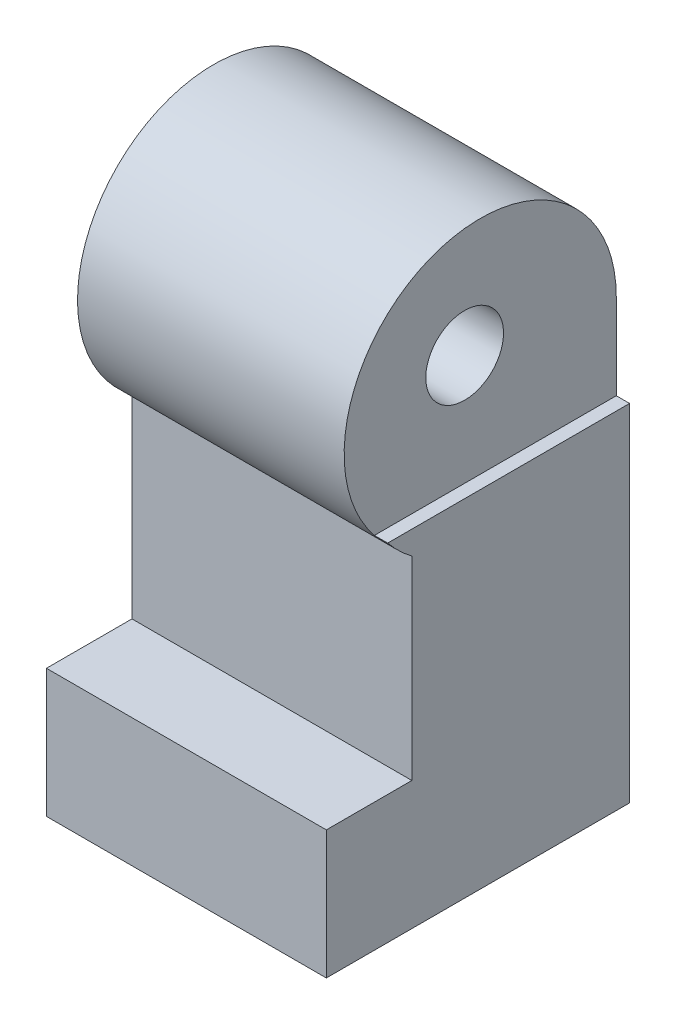
SolidWorks part; units mm, degrees
ref_plane "Alzado" through (0, 0, 0) normal (0, 0, 1) x (1, 0, 0)
ref_plane "Planta" through (0, 0, 0) normal (0, 1, 0) x (1, 0, 0)
ref_plane "Vista lateral" through (0, 0, 0) normal (1, 0, 0) x (0, 0, -1)
sketch "Croquis3" plane through (0, 0, 0) normal (1, 0, 0) x (0, 0, -1)
  line L0 (11.7, 11.4) -> (11.7, -21.9)
  line L1 (11.7, -21.9) -> (-11.7, -21.9)
  line L2 (-11.7, -21.9) -> (-11.7, -12)
  line L3 (-11.7, -12) -> (-5.1, -12)
  line L4 (-5.1, -12) -> (-5.1, 3)
  arc A0 (11.7, 11.4) -> (-5.1, 3) centre (1.2, 11.4) ccw
  dimension "D1" = 21
  dimension "D2" = 33.3
  dimension "D3" = 15
  dimension "D4" = 23.4
  dimension "D5" = 16.8
  dimension "D6" = 21.9
  dimension "D7" = 11.7
extrude "Saliente-Extruir1" add sketch "Croquis3" along normal mid plane 21.6
sketch "Croquis4" plane through (0, 0, 0) normal (0, 0, 1) x (1, 0, 0)
  line L1 (10.8, 21.9) -> (9.775, 21.9)
  line L2 (10.8, 21.9) -> (10.8, 4.8)
  line L3 (10.8, 4.8) -> (9.775, 4.8)
  line L4 (9.775, 21.9) -> (9.775, 4.8)
  dimension "D1" = 17.1
  dimension "D2" = 1.025
extrude "Cortar-Extruir1" cut sketch "Croquis4" against normal through all both and the other way through all
sketch "Croquis5" plane through (9.775, 0, 0) normal (1, 0, 0) x (0, 0, -1)
  line L0 (11.7, 4.8) -> (-6.9664, 4.8) construction
  line L1 (11.7, -21.9) -> (11.7, 4.8) construction
  circle A0 centre (0, 13.35) radius 3
  dimension "D1" = 6
  dimension "D2" = 8.55
  dimension "D3" = 11.7
extrude "Cortar-Extruir2" cut sketch "Croquis5" against normal blind 6.425 and the other way through all
